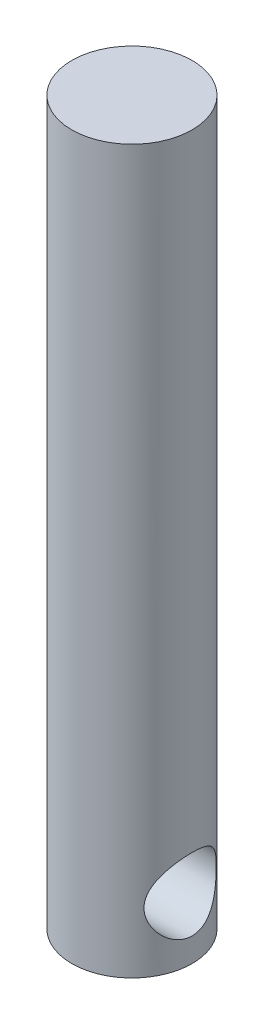
SolidWorks part; units mm, degrees
ref_plane "Front Plane" through (0, 0, 0) normal (0, 0, 1) x (1, 0, 0)
ref_plane "Top Plane" through (0, 0, 0) normal (0, 1, 0) x (1, 0, 0)
ref_plane "Right Plane" through (0, 0, 0) normal (1, 0, 0) x (0, 0, -1)
sketch "Sketch1" plane through (0, 0, 0) normal (0, 1, 0) x (1, 0, 0)
  circle A0 centre (0, 0) radius 2.5
  dimension "D1" = 5
extrude "Boss-Extrude1" add sketch "Sketch1" along normal blind 30
sketch "Sketch2" plane through (0, 0, 0) normal (1, 0, 0) x (0, 0, -1)
  circle A0 centre (0, 2.5) radius 1.5
  point P4 (0, 0)
  dimension "D1" = 3
  dimension "D2" = 2.5
extrude "Cut-Extrude1" cut sketch "Sketch2" against normal through all both and the other way through all
